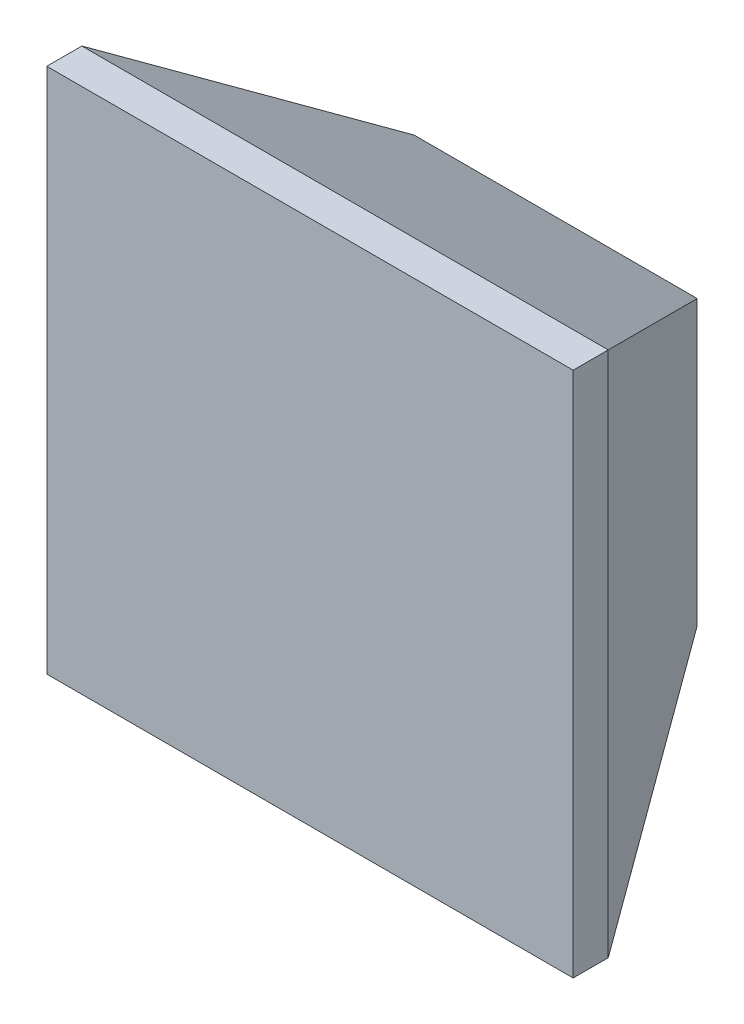
SolidWorks part; units mm, degrees
ref_plane "Front" through (0, 0, 0) normal (0, 0, 1) x (1, 0, 0)
ref_plane "Top" through (0, 0, 0) normal (0, 1, 0) x (1, 0, 0)
ref_plane "Right" through (0, 0, 0) normal (1, 0, 0) x (0, 0, -1)
sketch "Sketch1" plane through (0, 0, 0) normal (0, 0, 1) x (1, 0, 0)
  line L1 (-75, 75) -> (75, 75)
  line L2 (-75, 75) -> (-75, -75)
  line L3 (-75, -75) -> (75, -75)
  line L4 (75, 75) -> (75, -75)
extrude "Extrude1" add sketch "Sketch1" along normal blind 10 and the other way blind 60 draft 30 from vertex at -10
